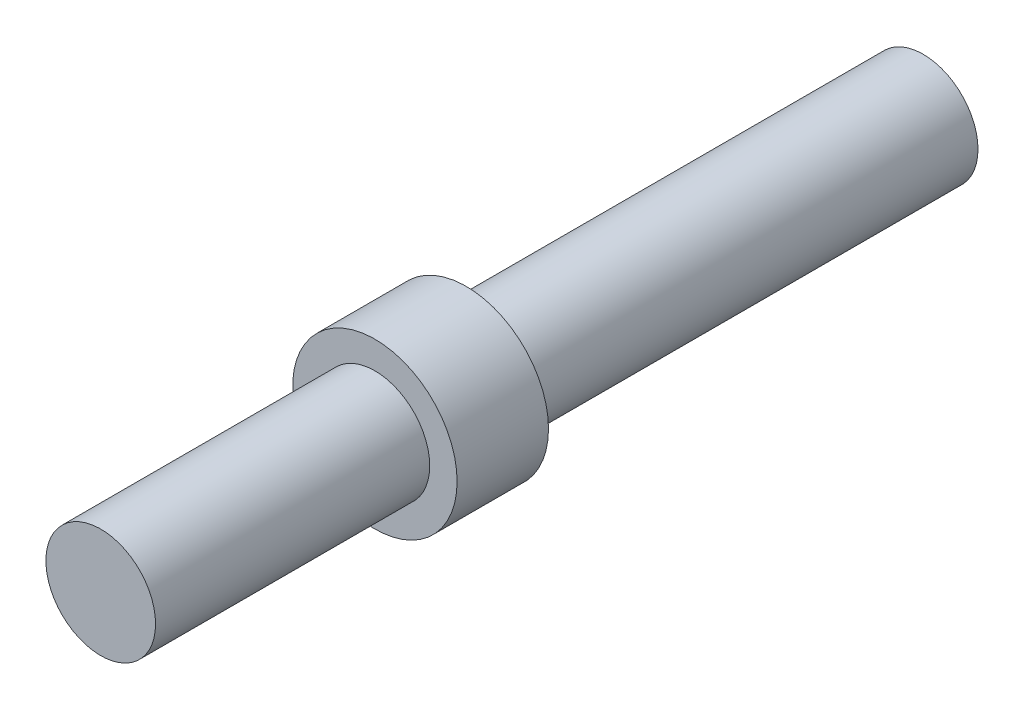
SolidWorks part; units mm, degrees
ref_plane "Front Plane" through (0, 0, 0) normal (0, 0, 1) x (1, 0, 0)
ref_plane "Top Plane" through (0, 0, 0) normal (0, 1, 0) x (1, 0, 0)
ref_plane "Right Plane" through (0, 0, 0) normal (1, 0, 0) x (0, 0, -1)
sketch "Sketch2" plane through (0, 0, 0) normal (0, 0, 1) x (1, 0, 0)
  circle A0 centre (0, 0) radius 6
  dimension "D1" = 12
extrude "Boss-Extrude1" add sketch "Sketch2" along normal blind 50
sketch "Sketch3" plane through (0, 0, 50) normal (0, 0, 1) x (1, 0, 0)
  circle A0 centre (0, 0) radius 9
  dimension "D1" = 18
extrude "Boss-Extrude2" add sketch "Sketch3" along normal blind 10
sketch "Sketch4" plane through (0, 0, 60) normal (0, 0, 1) x (1, 0, 0)
  circle A0 centre (0, 0) radius 6
  dimension "D1" = 12
extrude "Boss-Extrude3" add sketch "Sketch4" along normal blind 30
